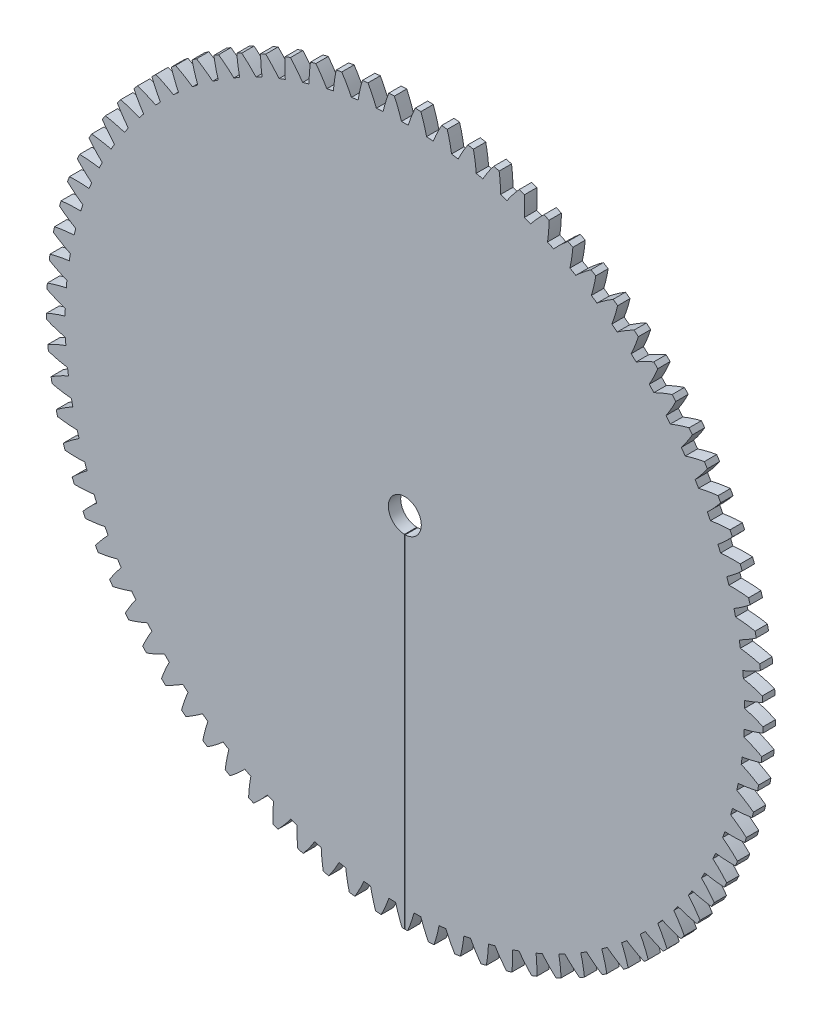
SolidWorks part; units mm, degrees
ref_plane "Plano frontal" through (0, 0, 0) normal (0, 0, 1) x (1, 0, 0)
ref_plane "Plano superior" through (0, 0, 0) normal (0, 1, 0) x (1, 0, 0)
ref_plane "Plano direito" through (0, 0, 0) normal (1, 0, 0) x (0, 0, -1)
sketch "Esboço1" plane through (0, 0, 0) normal (0, 0, 1) x (1, 0, 0)
  line L0 (0.1, -3.9987) -> (0.1, -86.9999)
  line L1 (-0.1, -3.9987) -> (-0.1, -86.9999)
  line L2 (0, 0) -> (0, 8.5463) construction
  arc A0 (0.1, -86.9999) -> (-0.1, -86.9999) centre (0, 0) ccw
  arc A1 (0.1, -3.9987) -> (-0.1, -3.9987) centre (0, 0) ccw
  dimension "D1" = 174
  dimension "D2" = 8
  dimension "D3" = 0.2
extrude "Ressalto-extrusão1" add sketch "Esboço1" along normal blind 3
sketch "Esboço2" plane through (0, 0, 3) normal (0, 0, 1) x (1, 0, 0)
  line L0 (0, 0) -> (0, 100.3814) construction
  line L1 (0, 0) -> (-1.688, 84.9832) construction
  line L2 (0, 0) -> (-6.2808, 169.8591) construction
  line L3 (-1.688, 84.9832) -> (-3.1404, 84.9295) construction
  arc A0 (0.8227, 82.4949) -> (-0.8227, 82.4949) centre (0, 0) ccw
  arc A1 (2.5486, 86.9881) -> (-2.5486, 86.9881) centre (0, 0) ccw
  circle A2 centre (0, 0) radius 85 construction
  circle A3 centre (0, 0) radius 79.8739 construction
  arc A4 (-0.8227, 82.4949) -> (-2.5486, 86.9881) centre (-33.3451, 72.5806) ccw
  arc A5 (2.5486, 86.9881) -> (0.8227, 82.4949) centre (33.3451, 72.5806) ccw
  dimension "D1" = 164.998
  dimension "D2" = 174.0508
  dimension "D3" = 170
  dimension "D6" = 159.7477
  dimension "D7" = 34
  dimension "D4" = 2.118
  dimension "D5" = 1.4535
extrude "Corte-extrusão1" cut sketch "Esboço2" against normal through all
pattern_circular "PadrãoCircular1" count 85 over 360 about axis through (0, 0, 0) along (0, 0, 1) of "Corte-extrusão1"
